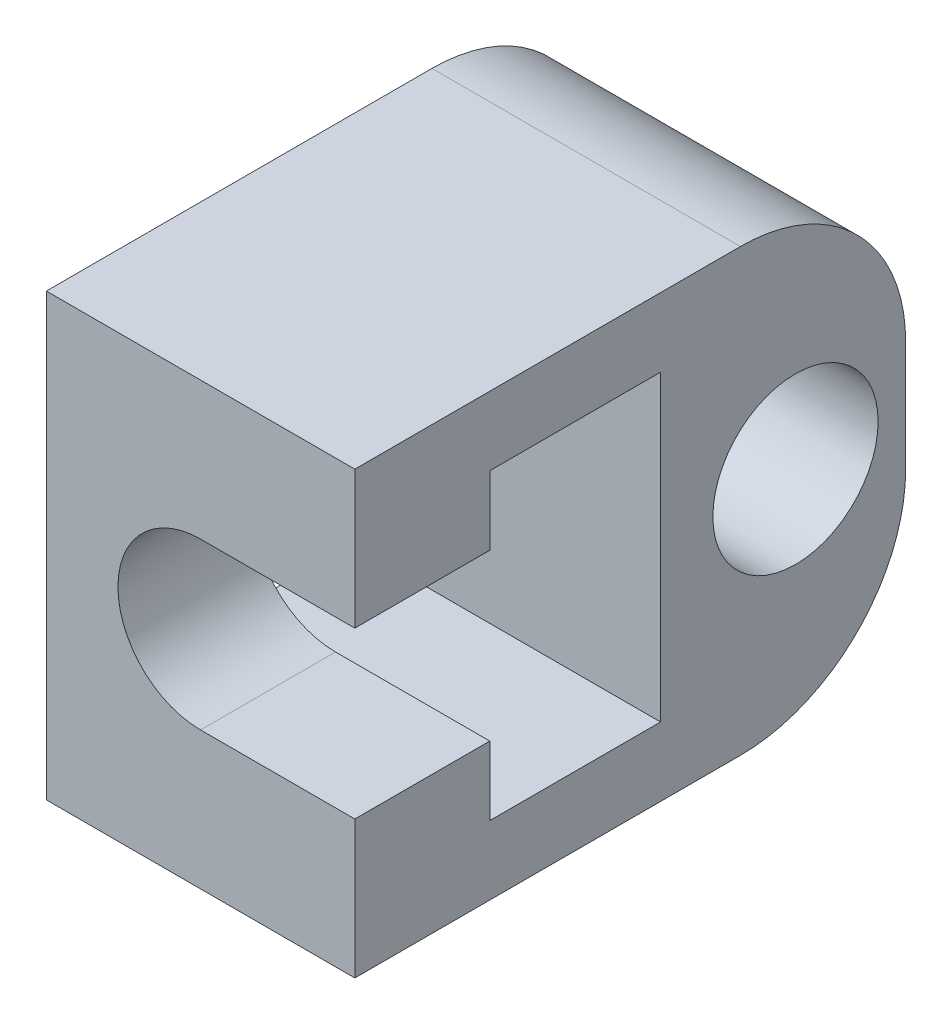
SolidWorks part; units mm, degrees
ref_plane "前视基准面" through (0, 0, 0) normal (0, 0, 1) x (1, 0, 0)
ref_plane "上视基准面" through (0, 0, 0) normal (0, 1, 0) x (1, 0, 0)
ref_plane "右视基准面" through (0, 0, 0) normal (1, 0, 0) x (0, 0, -1)
sketch "草图1" plane through (0, 0, 0) normal (0, 1, 0) x (1, 0, 0)
  line L1 (2.8, -5) -> (-2.8, -5)
  line L2 (2.8, -5) -> (2.8, 5)
  line L3 (2.8, 5) -> (-2.8, 5)
  line L4 (-2.8, -5) -> (-2.8, 5)
  line L5 (0, 5) -> (0, -5) construction
  line L6 (2.8, 0) -> (-2.8, 0) construction
  point P0 (0, 0)
  dimension "D1" = 10
  dimension "D2" = 5.6
extrude "凸台-拉伸1" add sketch "草图1" along normal blind 8
sketch "草图2" plane through (2.8, 0, 0) normal (1, 0, 0) x (0, 0, -1)
  line L0 (-1, 4) -> (-5, 4) construction
  line L1 (-2.55, 1.25) -> (0.55, 1.25)
  line L2 (-2.55, 1.25) -> (-2.55, 6.75)
  line L3 (-2.55, 6.75) -> (0.55, 6.75)
  line L4 (0.55, 1.25) -> (0.55, 6.75)
  line L5 (-1, 6.75) -> (-1, 1.25) construction
  line L6 (-2.55, 4) -> (0.55, 4) construction
  line L7 (-5, 8) -> (-5, 0) construction
  point P0 (-1, 4)
  dimension "D1" = 4
  dimension "D2" = 3.1
  dimension "D3" = 5.5
extrude "切除-拉伸1" cut sketch "草图2" against normal through all
sketch "草图3" plane through (0, 0, 5) normal (0, 0, 1) x (1, 0, 0)
  line L0 (0, 4) -> (2.8, 4) construction
  line L1 (2.8, 8) -> (2.8, 0) construction
  line L2 (0, 4) -> (0, 0) construction
  line L3 (0, 5.5) -> (2.8, 5.5)
  line L4 (2.8, 5.5) -> (2.8, 2.5)
  line L5 (2.8, 2.5) -> (0, 2.5)
  line L6 (2.8, 5.5) -> (2.8, 2.5)
  circle A0 centre (0, 4) radius 1.5
  line M6 (2.8, 0) -> (2.8, 8)
  dimension "D1" = 3
extrude "切除-拉伸2" cut sketch "草图3" against normal up to next contours A0 | A0 L5 L3 M6
sketch "草图4" plane through (2.8, 0, 0) normal (1, 0, 0) x (0, 0, -1)
  line L0 (5, 8) -> (5, 0) construction
  line L1 (3, 4) -> (5, 4) construction
  circle A0 centre (3, 4) radius 1.5
  dimension "D1" = 3
  dimension "D2" = 2
extrude "切除-拉伸3" cut sketch "草图4" against normal through all
fillet "圆角1" radius 3 2 edges at (0, 0, -5) (0, 8, -5)
